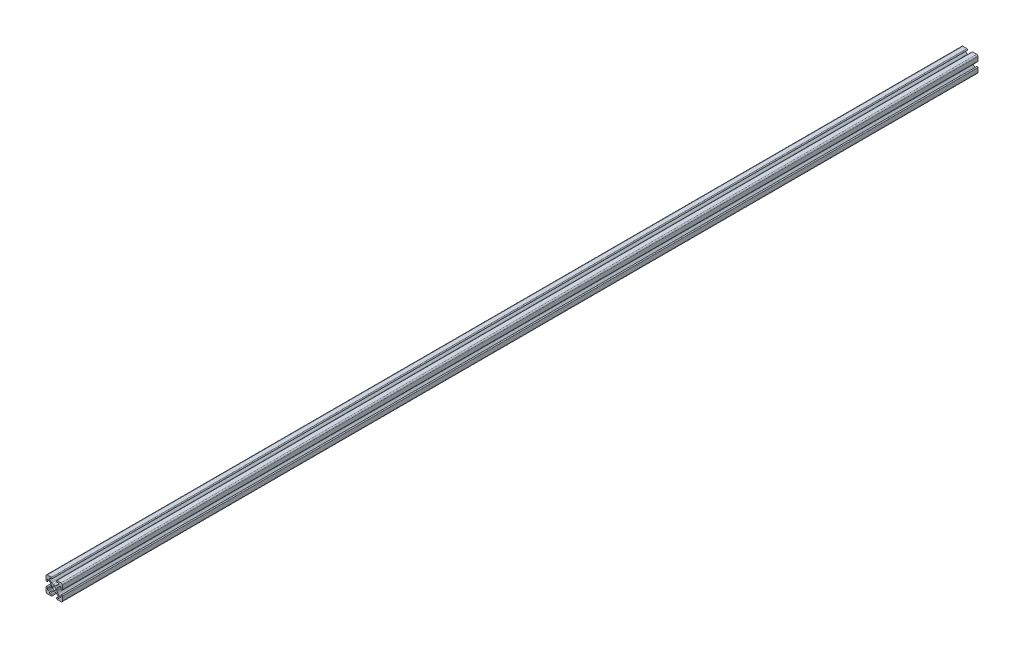
SolidWorks part; units mm, degrees
material "1060 Alloy"
ref_plane "Front Plane" through (0, 0, 0) normal (0, 0, 1) x (1, 0, 0)
ref_plane "Top Plane" through (0, 0, 0) normal (0, 1, 0) x (1, 0, 0)
ref_plane "Right Plane" through (0, 0, 0) normal (1, 0, 0) x (0, 0, -1)
ref_plane "Plane1" through (0, 0, -500) normal (0, 0, -1) x (-1, 0, 0)
sketch "Sketch1" plane through (0, 0, -500) normal (0, 0, -1) x (-1, 0, 0)
  line L0 (12.5, 4.32) -> (12.5, 10.5371)
  line L1 (10.5371, 12.5) -> (4.32, 12.5)
  line L2 (4.32, 10.36) -> (6.42, 10.36)
  line L3 (7.1337, 8.6353) -> (3.7953, 5.3018)
  line L4 (1.5554, 4.375) -> (-1.5554, 4.375)
  line L5 (-3.7953, 5.3018) -> (-7.1337, 8.6353)
  line L6 (-6.42, 10.36) -> (-4.32, 10.36)
  line L7 (-4.32, 12.5) -> (-10.5371, 12.5)
  line L8 (-12.5, 10.5371) -> (-12.5, 4.32)
  line L9 (-10.36, 4.32) -> (-10.36, 6.3969)
  line L10 (-8.6363, 7.1116) -> (-5.4322, 3.9121)
  line L11 (-4.455, 1.5554) -> (-4.455, -1.5554)
  line L12 (-5.4322, -3.9121) -> (-8.6363, -7.1116)
  line L13 (-10.36, -6.3969) -> (-10.36, -4.32)
  line L14 (-12.5, -4.32) -> (-12.5, -10.5371)
  line L15 (-10.5371, -12.5) -> (-4.3879, -12.5)
  line L16 (-4.3879, -10.36) -> (-6.42, -10.36)
  line L17 (-7.1337, -8.6353) -> (-3.7953, -5.3018)
  line L18 (-1.5554, -4.375) -> (1.5554, -4.375)
  line L19 (3.7953, -5.3018) -> (7.1337, -8.6353)
  line L20 (6.42, -10.36) -> (4.3879, -10.36)
  line L21 (4.3879, -12.5) -> (10.5371, -12.5)
  line L22 (12.5, -10.5371) -> (12.5, -4.32)
  line L23 (10.36, -4.32) -> (10.36, -6.3969)
  line L24 (8.6363, -7.1116) -> (5.4322, -3.9121)
  line L25 (4.455, -1.5554) -> (4.455, 1.5554)
  line L26 (5.4322, 3.9121) -> (8.6363, 7.1116)
  line L27 (10.36, 6.3969) -> (10.36, 4.32)
  circle A0 centre (0, 0) radius 2.5
  arc A1 (12.5, 10.5371) -> (10.5371, 12.5) centre (10.5371, 10.5371) ccw
  arc A2 (4.32, 12.5) -> (4.32, 10.36) centre (4.32, 11.43) ccw
  arc A3 (6.42, 10.36) -> (7.1337, 8.6353) centre (6.42, 9.35) cw
  arc A4 (3.7953, 5.3018) -> (1.5554, 4.375) centre (1.5554, 7.545) cw
  arc A5 (-1.5554, 4.375) -> (-3.7953, 5.3018) centre (-1.5554, 7.545) cw
  arc A6 (-7.1337, 8.6353) -> (-6.42, 10.36) centre (-6.42, 9.35) cw
  arc A7 (-4.32, 10.36) -> (-4.32, 12.5) centre (-4.32, 11.43) ccw
  arc A8 (-10.5371, 12.5) -> (-12.5, 10.5371) centre (-10.5371, 10.5371) ccw
  arc A9 (-12.5, 4.32) -> (-10.36, 4.32) centre (-11.43, 4.32) ccw
  arc A10 (-10.36, 6.3969) -> (-8.6363, 7.1116) centre (-9.35, 6.3969) cw
  arc A11 (-5.4322, 3.9121) -> (-4.455, 1.5554) centre (-7.7855, 1.5554) cw
  arc A12 (-4.455, -1.5554) -> (-5.4322, -3.9121) centre (-7.7855, -1.5554) cw
  arc A13 (-8.6363, -7.1116) -> (-10.36, -6.3969) centre (-9.35, -6.3969) cw
  arc A14 (-10.36, -4.32) -> (-12.5, -4.32) centre (-11.43, -4.32) ccw
  arc A15 (-12.5, -10.5371) -> (-10.5371, -12.5) centre (-10.5371, -10.5371) ccw
  arc A16 (-4.3879, -12.5) -> (-4.3879, -10.36) centre (-4.3879, -11.43) ccw
  arc A17 (-6.42, -10.36) -> (-7.1337, -8.6353) centre (-6.42, -9.35) cw
  arc A18 (-3.7953, -5.3018) -> (-1.5554, -4.375) centre (-1.5554, -7.545) cw
  arc A19 (1.5554, -4.375) -> (3.7953, -5.3018) centre (1.5554, -7.545) cw
  arc A20 (7.1337, -8.6353) -> (6.42, -10.36) centre (6.42, -9.35) cw
  arc A21 (4.3879, -10.36) -> (4.3879, -12.5) centre (4.3879, -11.43) ccw
  arc A22 (10.5371, -12.5) -> (12.5, -10.5371) centre (10.5371, -10.5371) ccw
  arc A23 (12.5, -4.32) -> (10.36, -4.32) centre (11.43, -4.32) ccw
  arc A24 (10.36, -6.3969) -> (8.6363, -7.1116) centre (9.35, -6.3969) cw
  arc A25 (5.4322, -3.9121) -> (4.455, -1.5554) centre (7.7855, -1.5554) cw
  arc A26 (4.455, 1.5554) -> (5.4322, 3.9121) centre (7.7855, 1.5554) cw
  arc A27 (8.6363, 7.1116) -> (10.36, 6.3969) centre (9.35, 6.3969) cw
  arc A28 (10.36, 4.32) -> (12.5, 4.32) centre (11.43, 4.32) ccw
extrude "Boss-Extrude1" add sketch "Sketch1" against normal blind 1400
